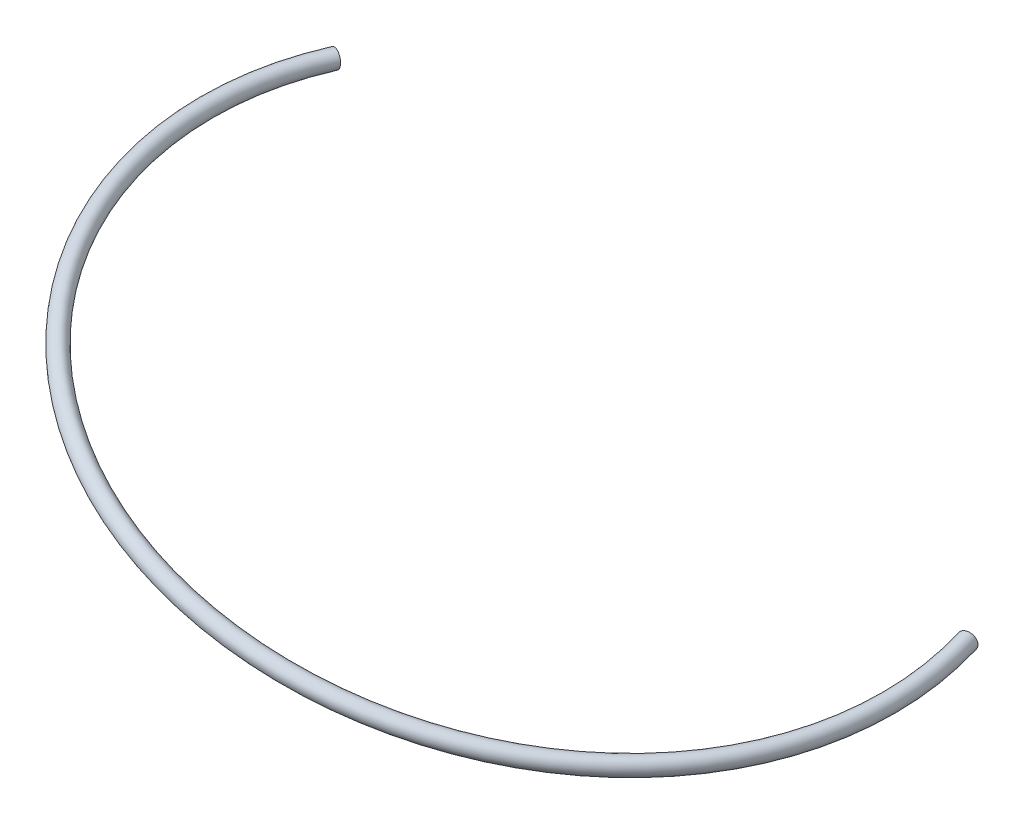
SolidWorks part; units mm, degrees
material "PVC 0.007 Plasticized"
ref_plane "Front Plane" through (0, 0, 0) normal (0, 0, 1) x (1, 0, 0)
ref_plane "Top Plane" through (0, 0, 0) normal (0, 1, 0) x (1, 0, 0)
ref_plane "Right Plane" through (0, 0, 0) normal (1, 0, 0) x (0, 0, -1)
sketch3d "3DSketch2"
  line L1 (240.75, -13.2, 11) -> (240.75, -13.2, 27) construction
  line L2 (88.75, 25.85, 6.25) -> (88.75, 25.85, 22.25) construction
  point P0 (88.75, 25.85, 22.25)
  point P1 (240.75, -13.2, 27)
  point P2 (88.75, 25.85, 22.25)
  point P4 (0, 0, 0)
ref_plane "Plane1" through (11.7249, 45.6384, 0) normal (0.2488, 0.9685, 0) x (0.9685, -0.2488, 0)
sketch "Sketch2" plane through (11.7249, 45.6384, 0) normal (0.2488, 0.9685, 0) x (0.9685, -0.2488, 0)
  arc A0 (79.5264, -22.25) -> (236.4624, -27) centre (157.2866, -48.0104) ccw
  dimension "D1" = 304.8
sweep "Sweep1" add path "Sketch2" circular profile diameter 4 parameters "D3"=4
